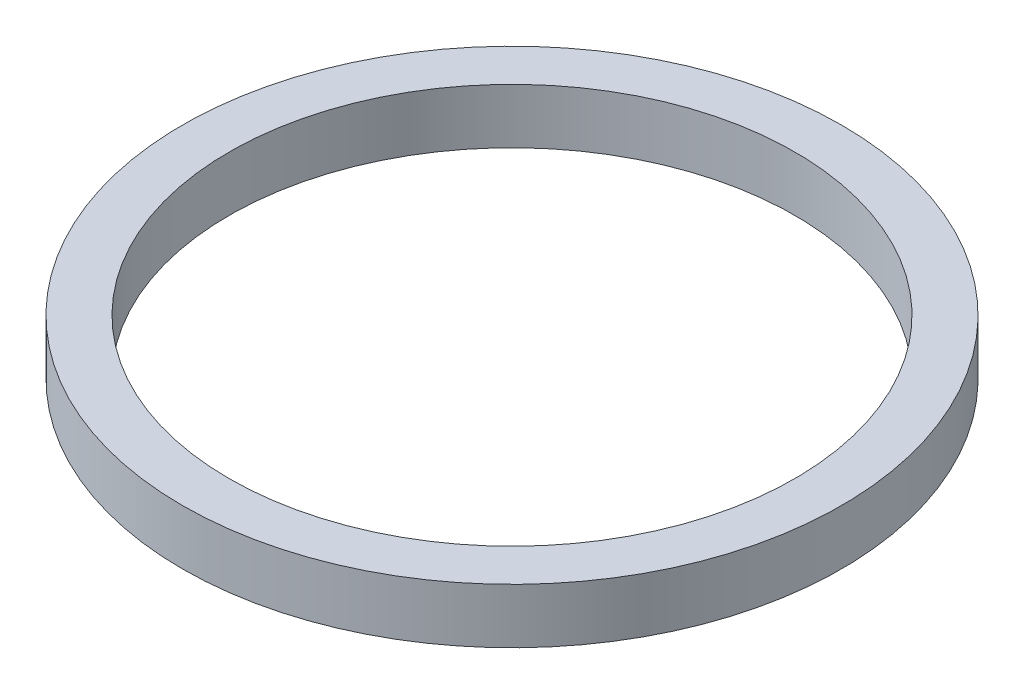
SolidWorks part; units mm, degrees
ref_plane "Front Plane" through (0, 0, 0) normal (0, 0, 1) x (1, 0, 0)
ref_plane "Top Plane" through (0, 0, 0) normal (0, 1, 0) x (1, 0, 0)
ref_plane "Right Plane" through (0, 0, 0) normal (1, 0, 0) x (0, 0, -1)
sketch "Sketch2" plane through (0, 0, 0) normal (0, 1, 0) x (1, 0, 0)
  circle A0 centre (0, 0) radius 13.081
  circle A1 centre (0, 0) radius 15.24
extrude "Boss-Extrude1" add sketch "Sketch2" along normal blind 2.54
